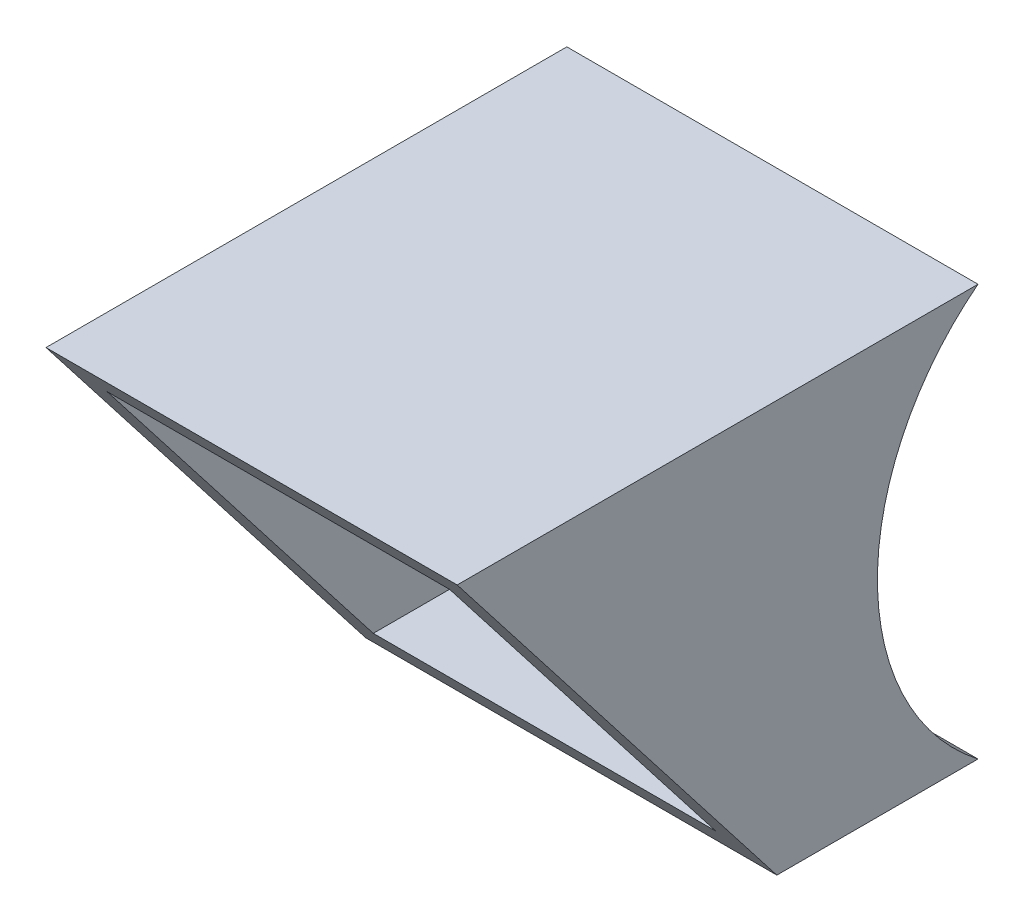
SolidWorks part; units mm, degrees
material "6063-T5"
ref_plane "Front Plane" through (0, 0, 0) normal (0, 0, 1) x (1, 0, 0)
ref_plane "Top Plane" through (0, 0, 0) normal (0, 1, 0) x (1, 0, 0)
ref_plane "Right Plane" through (0, 0, 0) normal (1, 0, 0) x (0, 0, -1)
sketch "Sketch1" plane through (0, 0, 0) normal (1, 0, 0) x (0, 0, -1)
  line L0 (0, 38.1) -> (29.6212, 0)
  line L1 (0, 0) -> (48.26, 0)
  line L2 (0, 0) -> (0, 38.1)
  line L3 (0, 38.1) -> (48.26, 38.1)
  line L4 (48.26, 0) -> (48.26, 38.1)
  circle A0 centre (63.0706, 19.05) radius 24.13
  dimension "D3" = 48.26
  dimension "D1" = 38.1
  dimension "D2" = 48.26
  dimension "D4" = 48.26
extrude "Boss-Extrude1" add sketch "Sketch1" along normal blind 38.1 contours A0 L3 L0 L1
sketch "Sketch2" plane through (0, 0, 0) normal (0, 0, 1) x (1, 0, 0)
  line L0 (3.175, 34.925) -> (3.175, 3.175)
  line L1 (3.175, 3.175) -> (34.925, 3.175)
  line L2 (34.925, 3.175) -> (34.925, 34.925)
  line L3 (34.925, 34.925) -> (3.175, 34.925)
  line L4 (0, 38.1) -> (0, 0)
  line L5 (0, 0) -> (38.1, 0)
  line L6 (38.1, 0) -> (38.1, 38.1)
  line L7 (38.1, 38.1) -> (0, 38.1)
  line L8 (0, 38.1) -> (0, 0) construction
  line L9 (0, 0) -> (38.1, 0) construction
  line L10 (38.1, 0) -> (38.1, 38.1) construction
  line L11 (38.1, 38.1) -> (0, 38.1) construction
  dimension "D1" = 0
  dimension "D2" = 3.175
extrude "Cut-Extrude1" cut sketch "Sketch2" against normal through all
